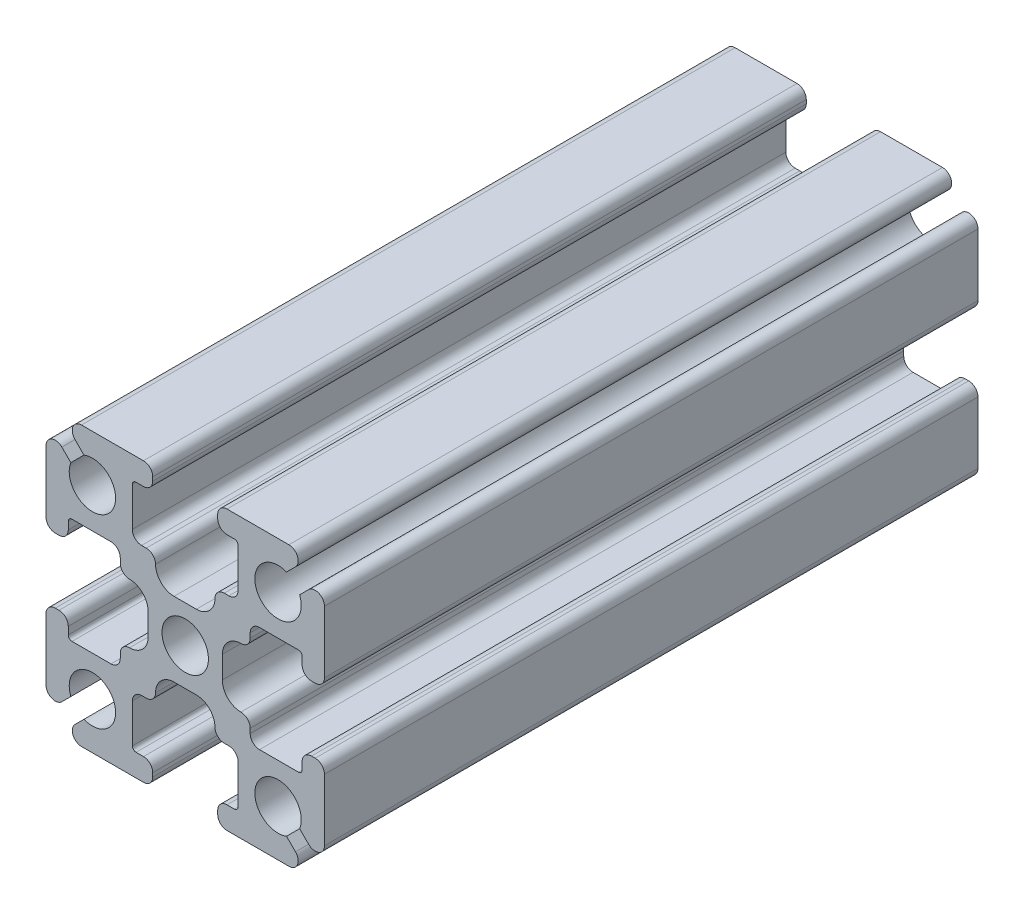
SolidWorks part; units mm, degrees
ref_plane "Front" through (0, 0, 0) normal (0, 0, 1) x (1, 0, 0)
ref_plane "Top" through (0, 0, 0) normal (0, 1, 0) x (1, 0, 0)
ref_plane "Right" through (0, 0, 0) normal (1, 0, 0) x (0, 0, -1)
sketch "Sketch1" plane through (0, 0, 0) normal (0, 0, 1) x (1, 0, 0)
  line L0 (6.6464, 5.9393) -> (6.1636, 5.4565)
  line L1 (5.4565, 6.1636) -> (5.9393, 6.6464)
  line L2 (5.5858, 7.5) -> (2.25, 7.5)
  line L3 (1.75, 7) -> (1.75, 6.8)
  line L4 (2.25, 6.3) -> (2.65, 6.3)
  line L5 (2.85, 6.1) -> (2.85, 4)
  line L6 (2.35, 3.5) -> (2.1, 3.5)
  line L7 (0.6, 2) -> (-0.6, 2)
  line L8 (-2.1, 3.5) -> (-2.35, 3.5)
  line L9 (-2.85, 4) -> (-2.85, 6.1)
  line L10 (-2.65, 6.3) -> (-2.25, 6.3)
  line L11 (-1.75, 6.8) -> (-1.75, 7)
  line L12 (-2.25, 7.5) -> (-5.5858, 7.5)
  line L13 (-5.9393, 6.6464) -> (-5.4565, 6.1636)
  line L14 (-6.1636, 5.4565) -> (-6.6464, 5.9393)
  line L15 (-7.5, 5.5858) -> (-7.5, 2.25)
  line L16 (-7, 1.75) -> (-6.8, 1.75)
  line L17 (-6.3, 2.25) -> (-6.3, 2.65)
  line L18 (-6.1, 2.85) -> (-4, 2.85)
  line L19 (-3.5, 2.35) -> (-3.5, 2.1)
  line L20 (-2, 0.6) -> (-2, -0.6)
  line L21 (-3.5, -2.1) -> (-3.5, -2.35)
  line L22 (-4, -2.85) -> (-6.1, -2.85)
  line L23 (-6.3, -2.65) -> (-6.3, -2.25)
  line L24 (-6.8, -1.75) -> (-7, -1.75)
  line L25 (-7.5, -2.25) -> (-7.5, -5.5858)
  line L26 (-6.6464, -5.9393) -> (-6.1636, -5.4565)
  line L27 (-5.4565, -6.1636) -> (-5.9393, -6.6464)
  line L28 (-5.5858, -7.5) -> (-2.25, -7.5)
  line L29 (-1.75, -7) -> (-1.75, -6.8)
  line L30 (-2.25, -6.3) -> (-2.65, -6.3)
  line L31 (-2.85, -6.1) -> (-2.85, -4)
  line L32 (-2.35, -3.5) -> (-2.1, -3.5)
  line L33 (-0.6, -2) -> (0.6, -2)
  line L34 (2.1, -3.5) -> (2.35, -3.5)
  line L35 (2.85, -4) -> (2.85, -6.1)
  line L36 (2.65, -6.3) -> (2.25, -6.3)
  line L37 (1.75, -6.8) -> (1.75, -7)
  line L38 (2.25, -7.5) -> (5.5858, -7.5)
  line L39 (5.9393, -6.6464) -> (5.4565, -6.1636)
  line L40 (6.1636, -5.4565) -> (6.6464, -5.9393)
  line L41 (7.5, -5.5858) -> (7.5, -2.25)
  line L42 (7, -1.75) -> (6.8, -1.75)
  line L43 (6.3, -2.25) -> (6.3, -2.65)
  line L44 (6.1, -2.85) -> (4, -2.85)
  line L45 (3.5, -2.35) -> (3.5, -2.1)
  line L46 (2, -0.6) -> (2, 0.6)
  line L47 (3.5, 2.1) -> (3.5, 2.35)
  line L48 (4, 2.85) -> (6.1, 2.85)
  line L49 (6.3, 2.65) -> (6.3, 2.25)
  line L50 (6.8, 1.75) -> (7, 1.75)
  line L51 (7.5, 2.25) -> (7.5, 5.5858)
  circle A0 centre (0, 0) radius 1.25
  arc A1 (6.1636, 5.4565) -> (5.4565, 6.1636) centre (5, 5) cw
  arc A2 (5.9393, 6.6464) -> (5.5858, 7.5) centre (5.5858, 7) ccw
  arc A3 (2.25, 7.5) -> (1.75, 7) centre (2.25, 7) ccw
  arc A4 (1.75, 6.8) -> (2.25, 6.3) centre (2.25, 6.8) ccw
  arc A5 (2.65, 6.3) -> (2.85, 6.1) centre (2.65, 6.1) cw
  arc A6 (2.85, 4) -> (2.35, 3.5) centre (2.35, 4) cw
  arc A7 (2.1, 3.5) -> (1.6, 3) centre (2.1, 3) ccw
  arc A8 (1.6, 3) -> (0.6, 2) centre (0.6, 3) cw
  arc A9 (-0.6, 2) -> (-1.6, 3) centre (-0.6, 3) cw
  arc A10 (-1.6, 3) -> (-2.1, 3.5) centre (-2.1, 3) ccw
  arc A11 (-2.35, 3.5) -> (-2.85, 4) centre (-2.35, 4) cw
  arc A12 (-2.85, 6.1) -> (-2.65, 6.3) centre (-2.65, 6.1) cw
  arc A13 (-2.25, 6.3) -> (-1.75, 6.8) centre (-2.25, 6.8) ccw
  arc A14 (-1.75, 7) -> (-2.25, 7.5) centre (-2.25, 7) ccw
  arc A15 (-5.5858, 7.5) -> (-5.9393, 6.6464) centre (-5.5858, 7) ccw
  arc A16 (-5.4565, 6.1636) -> (-6.1636, 5.4565) centre (-5, 5) cw
  arc A17 (-6.6464, 5.9393) -> (-7.5, 5.5858) centre (-7, 5.5858) ccw
  arc A18 (-7.5, 2.25) -> (-7, 1.75) centre (-7, 2.25) ccw
  arc A19 (-6.8, 1.75) -> (-6.3, 2.25) centre (-6.8, 2.25) ccw
  arc A20 (-6.3, 2.65) -> (-6.1, 2.85) centre (-6.1, 2.65) cw
  arc A21 (-4, 2.85) -> (-3.5, 2.35) centre (-4, 2.35) cw
  arc A22 (-3.5, 2.1) -> (-3, 1.6) centre (-3, 2.1) ccw
  arc A23 (-3, 1.6) -> (-2, 0.6) centre (-3, 0.6) cw
  arc A24 (-2, -0.6) -> (-3, -1.6) centre (-3, -0.6) cw
  arc A25 (-3, -1.6) -> (-3.5, -2.1) centre (-3, -2.1) ccw
  arc A26 (-3.5, -2.35) -> (-4, -2.85) centre (-4, -2.35) cw
  arc A27 (-6.1, -2.85) -> (-6.3, -2.65) centre (-6.1, -2.65) cw
  arc A28 (-6.3, -2.25) -> (-6.8, -1.75) centre (-6.8, -2.25) ccw
  arc A29 (-7, -1.75) -> (-7.5, -2.25) centre (-7, -2.25) ccw
  arc A30 (-7.5, -5.5858) -> (-6.6464, -5.9393) centre (-7, -5.5858) ccw
  arc A31 (-6.1636, -5.4565) -> (-5.4565, -6.1636) centre (-5, -5) cw
  arc A32 (-5.9393, -6.6464) -> (-5.5858, -7.5) centre (-5.5858, -7) ccw
  arc A33 (-2.25, -7.5) -> (-1.75, -7) centre (-2.25, -7) ccw
  arc A34 (-1.75, -6.8) -> (-2.25, -6.3) centre (-2.25, -6.8) ccw
  arc A35 (-2.65, -6.3) -> (-2.85, -6.1) centre (-2.65, -6.1) cw
  arc A36 (-2.85, -4) -> (-2.35, -3.5) centre (-2.35, -4) cw
  arc A37 (-2.1, -3.5) -> (-1.6, -3) centre (-2.1, -3) ccw
  arc A38 (-1.6, -3) -> (-0.6, -2) centre (-0.6, -3) cw
  arc A39 (0.6, -2) -> (1.6, -3) centre (0.6, -3) cw
  arc A40 (1.6, -3) -> (2.1, -3.5) centre (2.1, -3) ccw
  arc A41 (2.35, -3.5) -> (2.85, -4) centre (2.35, -4) cw
  arc A42 (2.85, -6.1) -> (2.65, -6.3) centre (2.65, -6.1) cw
  arc A43 (2.25, -6.3) -> (1.75, -6.8) centre (2.25, -6.8) ccw
  arc A44 (1.75, -7) -> (2.25, -7.5) centre (2.25, -7) ccw
  arc A45 (5.5858, -7.5) -> (5.9393, -6.6464) centre (5.5858, -7) ccw
  arc A46 (5.4565, -6.1636) -> (6.1636, -5.4565) centre (5, -5) cw
  arc A47 (6.6464, -5.9393) -> (7.5, -5.5858) centre (7, -5.5858) ccw
  arc A48 (7.5, -2.25) -> (7, -1.75) centre (7, -2.25) ccw
  arc A49 (6.8, -1.75) -> (6.3, -2.25) centre (6.8, -2.25) ccw
  arc A50 (6.3, -2.65) -> (6.1, -2.85) centre (6.1, -2.65) cw
  arc A51 (4, -2.85) -> (3.5, -2.35) centre (4, -2.35) cw
  arc A52 (3.5, -2.1) -> (3, -1.6) centre (3, -2.1) ccw
  arc A53 (3, -1.6) -> (2, -0.6) centre (3, -0.6) cw
  arc A54 (2, 0.6) -> (3, 1.6) centre (3, 0.6) cw
  arc A55 (3, 1.6) -> (3.5, 2.1) centre (3, 2.1) ccw
  arc A56 (3.5, 2.35) -> (4, 2.85) centre (4, 2.35) cw
  arc A57 (6.1, 2.85) -> (6.3, 2.65) centre (6.1, 2.65) cw
  arc A58 (6.3, 2.25) -> (6.8, 1.75) centre (6.8, 2.25) ccw
  arc A59 (7, 1.75) -> (7.5, 2.25) centre (7, 2.25) ccw
  arc A60 (7.5, 5.5858) -> (6.6464, 5.9393) centre (7, 5.5858) ccw
extrude "Boss-Extrude1" add sketch "Sketch1" along normal blind 35.205
